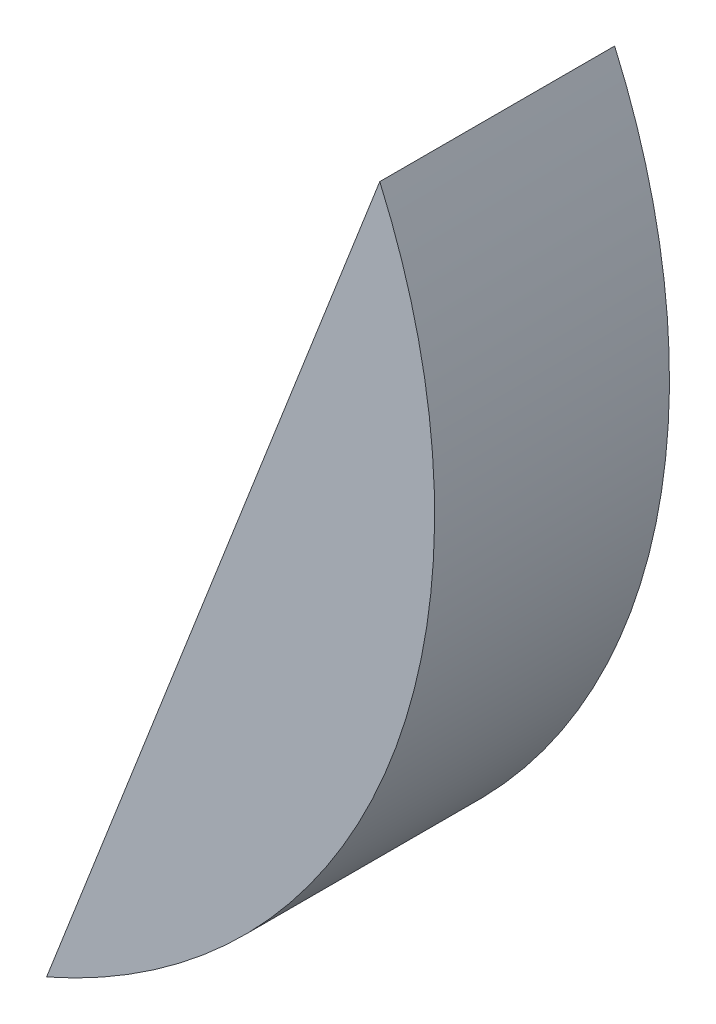
SolidWorks part; units mm, degrees
ref_plane "Front Plane" through (0, 0, 0) normal (0, 0, 1) x (1, 0, 0)
ref_plane "Top Plane" through (0, 0, 0) normal (0, 1, 0) x (1, 0, 0)
ref_plane "Right Plane" through (0, 0, 0) normal (1, 0, 0) x (0, 0, -1)
sketch "CurveSketch" plane through (0, 0, 0) normal (0, 0, 1) x (1, 0, 0)
  line L0 (2.7998, -4.3453) -> (12.9273, 21.6558)
  arc A0 (12.9273, 21.6558) -> (2.7998, -4.3453) centre (-5.137, 13.719) cw
  dimension "D1" = 19.731
extrude "CurveBoss" add sketch "CurveSketch" along normal blind 7.139
